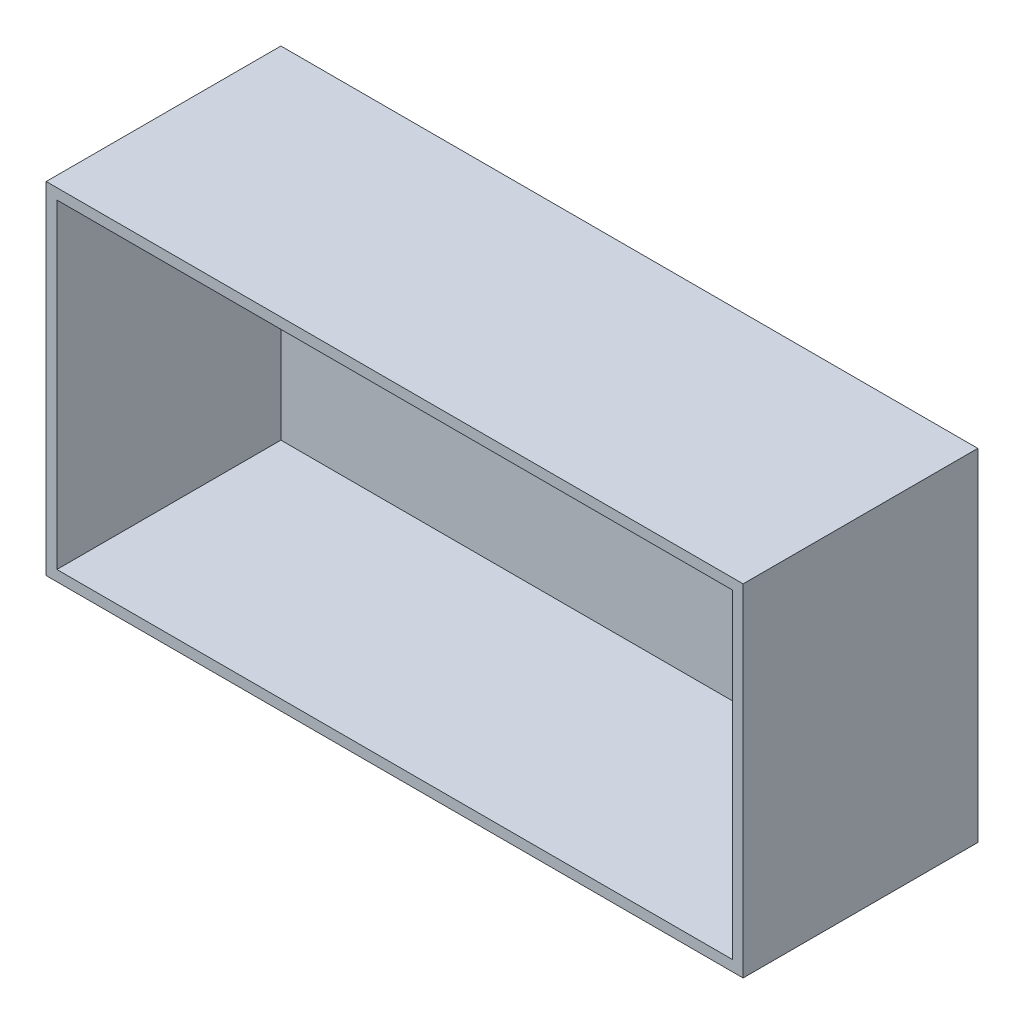
SolidWorks part; units mm, degrees
ref_plane "Front Plane" through (0, 0, 0) normal (0, 0, 1) x (1, 0, 0)
ref_plane "Top Plane" through (0, 0, 0) normal (0, 1, 0) x (1, 0, 0)
ref_plane "Right Plane" through (0, 0, 0) normal (1, 0, 0) x (0, 0, -1)
sketch "Sketch1" plane through (0, 0, 0) normal (0, 0, 1) x (1, 0, 0)
  line L1 (0, 0) -> (196, 0)
  line L2 (0, 0) -> (0, 96)
  line L3 (0, 96) -> (196, 96)
  line L4 (196, 0) -> (196, 96)
  line L5 (3, 3) -> (193, 3)
  line L6 (3, 3) -> (3, 93)
  line L7 (3, 93) -> (193, 93)
  line L8 (193, 3) -> (193, 93)
  dimension "D1" = 3
  dimension "D2" = 193
  dimension "D3" = 196
  dimension "D4" = 3
  dimension "D5" = 93
  dimension "D6" = 96
extrude "Profile" add sketch "Sketch1" along normal blind 66
sketch "Sketch2" plane through (0, 0, 0) normal (0, 0, 1) x (1, 0, 0)
  line L1 (3, 3) -> (193, 3)
  line L2 (3, 3) -> (3, 93)
  line L3 (3, 93) -> (193, 93)
  line L4 (193, 3) -> (193, 93)
extrude "Back" add sketch "Sketch2" along normal blind 3
equation "\"Profile_Depth\" = 66mm"
equation "\"D1@Profile\" = \"Profile_Depth\""
equation "\"Back_Depth\" = 3mm"
equation "\"D1@Back\" = \"Back_Depth\""
equation "\"EnvelopeWidth\" = 196mm"
equation "\"EnvelopeHeight\" = 96mm"
